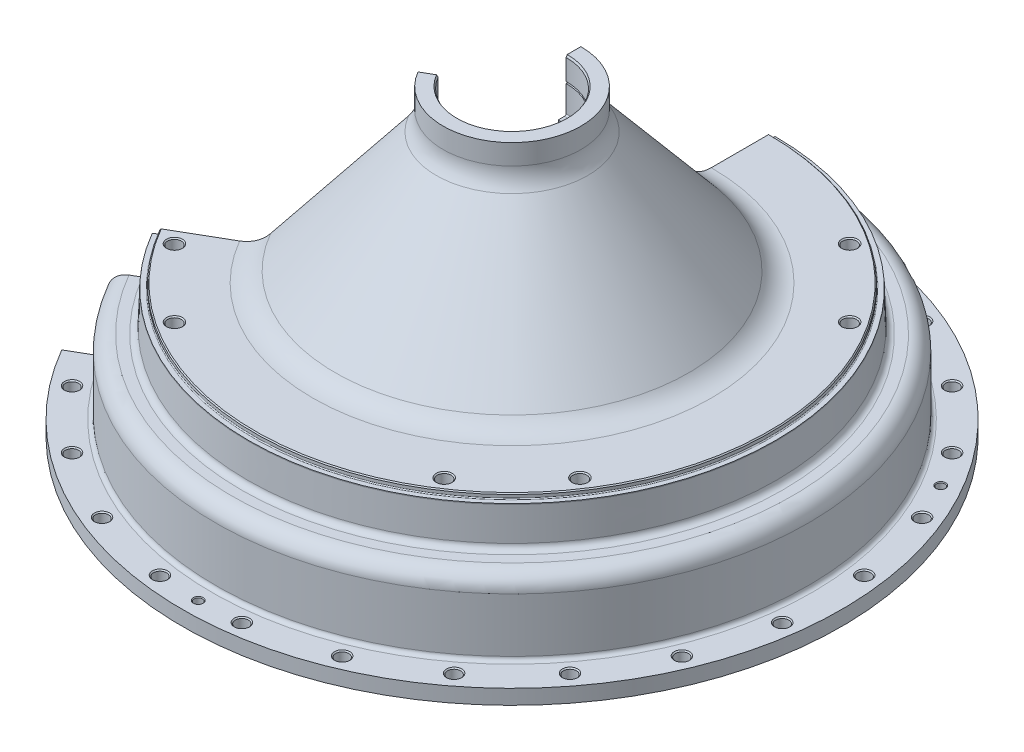
SolidWorks part; units mm, degrees
ref_plane "Front Plane" through (0, 0, 0) normal (0, 0, 1) x (1, 0, 0)
ref_plane "Top Plane" through (0, 0, 0) normal (0, 1, 0) x (1, 0, 0)
ref_plane "Right Plane" through (0, 0, 0) normal (1, 0, 0) x (0, 0, -1)
sketch "Sketch1" plane through (0, 0, 0) normal (0, 0, 1) x (1, 0, 0)
  line L0 (267.6219, 299) -> (0, 299)
  line L1 (0, 299) -> (0, 169)
  line L2 (0, 169) -> (335, 169)
  line L3 (335, 169) -> (335, 184)
  line L4 (335, 184) -> (301, 184)
  line L5 (301, 184) -> (301, 259)
  line L6 (301, 259) -> (269.0714, 259)
  line L7 (269.0714, 259) -> (267.7022, 298.2094)
  line L8 (0, 299) -> (0, 169) construction
  arc A0 (267.7022, 298.2094) -> (267.6219, 299) centre (261.7059, 298) ccw
revolve "Revolve1" add sketch "Sketch1" angle 360 about L8
sketch "Sketch2" plane through (0, 299, 0) normal (0, 1, 0) x (-1, 0, 0)
  circle A0 centre (0, 0) radius 262
extrude "Boss-Extrude1" add sketch "Sketch2" along normal blind 5
sketch "Sketch3" plane through (0, 304, 0) normal (0, 1, 0) x (-1, 0, 0)
  circle A0 centre (0, 0) radius 188.6694
extrude "Boss-Extrude2" add sketch "Sketch3" along normal blind 141.4247 draft 40
sketch "Sketch4" plane through (0, 445.4247, 0) normal (0, 1, 0) x (-1, 0, 0)
  circle A0 centre (0, 0) radius 70
extrude "Boss-Extrude3" add sketch "Sketch4" along normal blind 31.5753
sketch "Sketch5" plane through (0, 169, 0) normal (0, -1, 0) x (1, 0, 0)
  circle A0 centre (0, 0) radius 300
extrude "Boss-Extrude4" add sketch "Sketch5" along normal blind 6
sketch "Sketch6" plane through (0, 163, 0) normal (0, -1, 0) x (1, 0, 0)
  circle A0 centre (0, 0) radius 295
extrude "Cut-Extrude1" cut sketch "Sketch6" against normal blind 26.6908
sketch "Sketch7" plane through (0, 189.6908, 0) normal (0, -1, 0) x (1, 0, 0)
  circle A0 centre (0, 0) radius 295
extrude "Cut-Extrude2" cut sketch "Sketch7" against normal blind 26.8092 draft 43
sketch "Sketch8" plane through (0, 0, 0) normal (0, 0, 1) x (1, 0, 0)
  line L0 (112, 216.5) -> (0, 216.5)
  line L1 (0, 216.5) -> (0, 204)
  line L2 (0, 204) -> (112, 204)
  line L3 (112, 204) -> (112, 216.5)
  line L4 (0, 216.5) -> (0, 204) construction
revolve "Revolve2" add sketch "Sketch8" angle 360 about L4
sketch "Sketch9" plane through (0, 0, 0) normal (0, 0, 1) x (1, 0, 0)
  line L0 (55, 477) -> (0, 477)
  line L1 (0, 477) -> (0, 204)
  line L2 (0, 204) -> (101.7321, 204)
  line L3 (101.7321, 204) -> (100, 207)
  line L4 (100, 207) -> (100, 208.55)
  line L5 (100, 208.55) -> (102.57, 208.55)
  line L6 (102.57, 208.55) -> (102.57, 210.95)
  line L7 (102.57, 210.95) -> (100, 210.95)
  line L8 (100, 210.95) -> (100, 249)
  line L9 (100, 249) -> (93, 249)
  line L10 (93, 249) -> (93, 251)
  line L11 (93, 251) -> (88.7085, 251)
  line L12 (86, 257) -> (86, 264)
  line L13 (86, 264) -> (55, 281.8979)
  line L14 (55, 281.8979) -> (55, 417)
  line L15 (55, 417) -> (47, 417)
  line L16 (47, 417) -> (47, 424)
  line L17 (47, 424) -> (55, 424)
  line L18 (55, 424) -> (55, 452.1)
  line L19 (55, 452.1) -> (56.655, 452.1)
  line L20 (56.655, 452.1) -> (56.655, 453.83)
  line L21 (56.655, 453.83) -> (55, 453.83)
  line L22 (55, 453.83) -> (55, 477)
  line L23 (0, 477) -> (0, 204) construction
  arc A0 (88.7085, 251) -> (86, 257) centre (94, 257) cw
revolve "Cut-Revolve1" cut sketch "Sketch9" angle 360 about L23
hole_wizard "M12 Clearance Hole1" positions "Sketch11" profile "Sketch10" hole size "M12" standard "ANSI Metric"
sketch "Sketch11" plane through (0, 184, 0) normal (0, 1, 0) x (1, 0, 0)
  point P0 (122.076, 294.7176)
  point P1 (-41.6379, 316.2709)
  point P2 (-122.076, 294.7176)
  point P3 (-194.1949, 253.0797)
  point P4 (-253.0797, 194.1949)
  point P5 (-294.7176, 122.076)
  point P6 (-316.2709, 41.6379)
sketch "Sketch10" plane through (122.076, 184, -294.7176) normal (1, 0, 0) x (0, 0, 1)
  line L0 (0, 0) -> (0, 21)
  line L1 (0, 21) -> (6.625, 21)
  line L2 (6.625, 21) -> (6.625, 0)
  line L5 (6.625, 0) -> (0, 0)
  line L11 (0, -6.35) -> (0, 107.95) construction
  dimension "Thru Hole Dia." = 13.25
  dimension "Thru Hole Depth" = 21
hole_wizard "M12 Clearance Hole2" positions "Sketch13" profile "Sketch12" hole size "M12" standard "ANSI Metric"
sketch "Sketch13" plane through (0, 169, 0) normal (0, -1, 0) x (-1, 0, 0)
  point P0 (-316.2709, -41.6379)
  point P1 (-316.2709, 41.6379)
  point P2 (-294.7176, -122.076)
  point P3 (-294.7176, 122.076)
  point P4 (-253.0797, -194.1949)
  point P5 (-253.0797, 194.1949)
  point P6 (-194.1949, -253.0797)
  point P7 (-194.1949, 253.0797)
  point P8 (-122.076, -294.7176)
  point P9 (-41.6379, -316.2709)
  point P10 (-41.6379, 316.2709)
  point P11 (41.6379, -316.2709)
  point P12 (122.076, -294.7176)
  point P13 (194.1949, -253.0797)
  point P14 (253.0797, -194.1949)
  point P15 (294.7176, -122.076)
  point P16 (316.2709, -41.6379)
sketch "Sketch12" plane through (316.2709, 169, 41.6379) normal (1, 0, 0) x (0, 0, -1)
  line L0 (0, 0) -> (0, 308)
  line L1 (0, 308) -> (6.625, 308)
  line L2 (6.625, 308) -> (6.625, 0)
  line L5 (6.625, 0) -> (0, 0)
  line L11 (0, -6.35) -> (0, 107.95) construction
  dimension "Thru Hole Dia." = 13.25
  dimension "Thru Hole Depth" = 308
hole_wizard "Ø8.5 (8.5) Diameter Hole1" positions "Sketch15" profile "Sketch14" hole size "Ø8.5" standard "ANSI Metric"
sketch "Sketch15" plane through (0, 169, 0) normal (0, -1, 0) x (-1, 0, 0)
  point P0 (0, -319)
sketch "Sketch14" plane through (0, 169, 319) normal (1, 0, 0) x (0, 0, -1)
  line L0 (0, 0) -> (0, 308)
  line L1 (0, 308) -> (4.25, 308)
  line L2 (4.25, 308) -> (4.25, 0)
  line L5 (4.25, 0) -> (0, 0)
  line L11 (0, -6.35) -> (0, 107.95) construction
  dimension "Thru Hole Dia." = 8.5
  dimension "Thru Hole Depth" = 308
hole_wizard "Ø8.5 (8.5) Diameter Hole2" positions "Sketch17" profile "Sketch16" hole size "Ø8.5" standard "ANSI Metric"
sketch "Sketch17" plane through (0, 184, 0) normal (0, 1, 0) x (1, 0, 0)
  point P0 (276.2621, 159.5)
  point P1 (-276.2621, 159.5)
sketch "Sketch16" plane through (276.2621, 184, -159.5) normal (1, 0, 0) x (0, 0, 1)
  line L0 (0, 0) -> (0, 21)
  line L1 (0, 21) -> (4.25, 21)
  line L2 (4.25, 21) -> (4.25, 0)
  line L5 (4.25, 0) -> (0, 0)
  line L11 (0, -6.35) -> (0, 107.95) construction
  dimension "Thru Hole Dia." = 8.5
  dimension "Thru Hole Depth" = 21
hole_wizard "Ø14.0 (14) Diameter Hole1" positions "Sketch19" profile "Sketch18" hole size "Ø14.0" standard "ANSI Metric"
sketch "Sketch19" plane through (0, 304, 0) normal (0, 1, 0) x (1, 0, 0)
  point P0 (206.0643, -137.0904)
  point P1 (206.0643, 137.0904)
  point P2 (137.0904, -206.0643)
  point P3 (137.0904, 206.0643)
  point P4 (-137.0904, -206.0643)
  point P5 (-137.0904, 206.0643)
  point P6 (-206.0643, -137.0904)
  point P7 (-206.0643, 137.0904)
sketch "Sketch18" plane through (206.0643, 304, 137.0904) normal (1, 0, 0) x (0, 0, 1)
  line L0 (0, 0) -> (0, 50.206)
  line L1 (0, 50.206) -> (7, 46)
  line L2 (7, 46) -> (7, 0)
  line L5 (7, 0) -> (0, 0)
  line L10 (0, 50.206) -> (-7, 46) construction
  line L11 (0, -6.35) -> (0, 107.95) construction
  dimension "Hole Dia." = 14
  dimension "Hole Depth" = 46
  dimension "Drill Angle" = 118
chamfer "Chamfer1" distance 1.1 angle 45 56 edges at (122.076, 169, -301.3426) (206.0643, 304, 144.0904) (-194.1949, 169, -259.7047) (194.1949, 184, 259.7047) (194.1949, 184, -246.4547) (-41.6379, 169, -322.8959) (122.076, 184, 301.3426) (-294.7176, 169, -128.701) (122.076, 184, -288.0926) (294.7176, 184, -115.451) (41.6379, 184, 322.8959) (253.0797, 184, -187.5699) (41.6379, 184, -309.6459) (41.6379, 169, -322.8959) (-41.6379, 184, 322.8959) (-122.076, 169, -301.3426) (-41.6379, 184, -309.6459) (-253.0797, 169, -200.8199) (-122.076, 184, 301.3426) (-316.2709, 169, -48.2629) (-122.076, 184, -288.0926) (206.0643, 304, -130.0904) (-194.1949, 184, 259.7047) (-206.0643, 304, 144.0904) (-194.1949, 184, -246.4547) (-253.0797, 184, 200.8199) (122.076, 169, 288.0926) (-253.0797, 184, -187.5699) (41.6379, 169, 309.6459) (-294.7176, 184, 128.701) (-41.6379, 169, 309.6459) (-294.7176, 184, -115.451) (-122.076, 169, 288.0926) (-316.2709, 184, 48.2629) (-194.1949, 169, 246.4547) (-316.2709, 184, -35.0129) (-253.0797, 169, 187.5699) (-294.7176, 169, 115.451) (-316.2709, 169, 35.0129) (316.2709, 184, 48.2629) (294.7176, 184, 128.701) (137.0904, 304, -199.0643) (-137.0904, 304, 213.0643) (294.7176, 169, 115.451) (-137.0904, 304, -199.0643) (294.7176, 169, -128.701) (-206.0643, 304, -130.0904) (316.2709, 184, -35.0129) (253.0797, 184, 200.8199) (194.1949, 169, 246.4547) (194.1949, 169, -259.7047) (253.0797, 169, 187.5699) (253.0797, 169, -200.8199) (137.0904, 304, 213.0643) (316.2709, 169, 35.0129) (316.2709, 169, -48.2629)
chamfer "Chamfer2" distance 1.1547 angle 60 1 edges at (0, 477, -55)
chamfer "Chamfer3" distance 0.75 angle 45 6 edges at (0, 184, 323.25) (276.2621, 169, -163.75) (0, 169, 314.75) (-276.2621, 169, -163.75) (276.2621, 184, -155.25) (-276.2621, 184, -155.25)
chamfer "Chamfer4" distance 0.866 angle 60 1 edges at (0, 163, -300)
chamfer "Chamfer5" distance 0.9934 angle 46.519 1 edges at (0, 304, 262)
fillet "Fillet1" radius 0.8 1 edges at (0, 169, -300)
fillet "Fillet2" radius 1 1 edges at (0, 299, 262)
fillet "Fillet3" radius 1.5 1 edges at (0, 424, -55)
fillet "Fillet4" radius 2.2 1 edges at (0, 249, -100)
fillet "Fillet5" radius 3 1 edges at (0, 204, -112)
fillet "Fillet6" radius 4 1 edges at (0, 184, -301)
fillet "Fillet7" radius 6 3 edges at (0, 259, -269.0714) (0, 189.6908, 295) (0, 216.5, -112)
fillet "Fillet8" radius 7 1 edges at (0, 417, -55)
fillet "Fillet9" radius 8 1 edges at (0, 264, -86)
fillet "Fillet10" radius 10 1 edges at (0, 281.8979, -55)
fillet "Fillet11" radius 16 1 edges at (0, 259, -301)
fillet "Fillet12" radius 18 1 edges at (0, 216.5, 270)
fillet "Fillet13" radius 30 2 edges at (0, 445.4247, 70) (0, 304, 188.6694)
sketch "Sketch20" plane through (0, 477, 0) normal (0, 1, 0) x (1, 0, 0)
  line L0 (0, 0) -> (-812.5248, -470.1925)
  line L1 (-812.5248, -470.1925) -> (-0.8858, 888.1851)
  line L2 (-0.8858, 888.1851) -> (0, 0)
  dimension "D1" = 120
extrude "Cut-Extrude3" cut sketch "Sketch20" against normal through all
